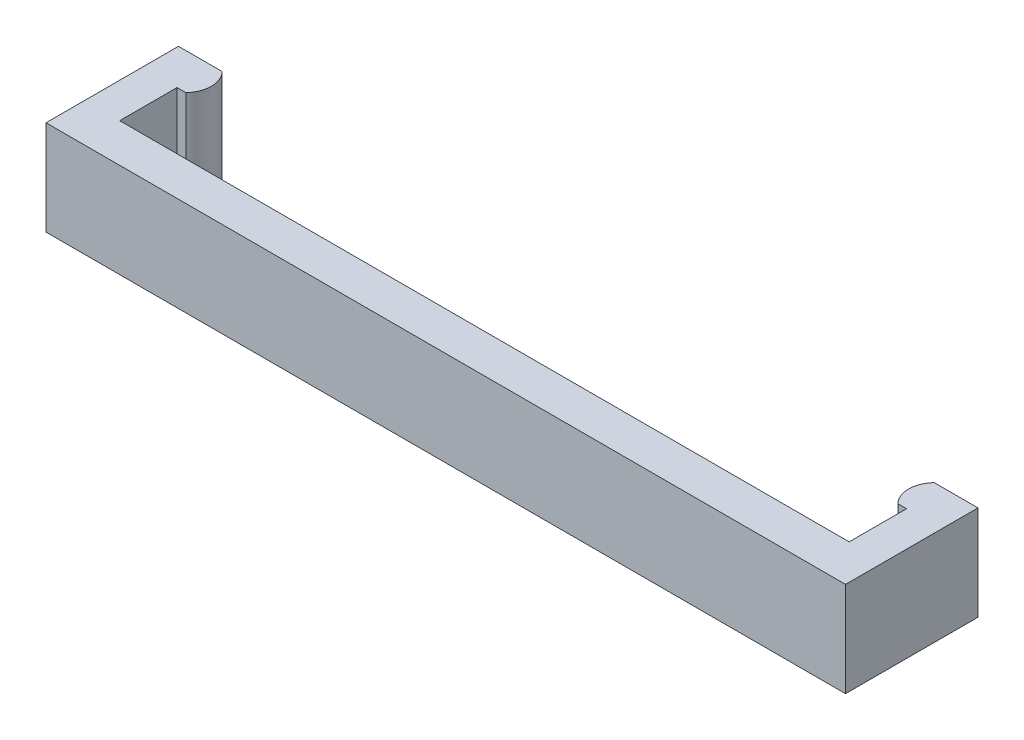
SolidWorks part; units mm, degrees
ref_plane "Front Plane" through (0, 0, 0) normal (0, 0, 1) x (1, 0, 0)
ref_plane "Top Plane" through (0, 0, 0) normal (0, 1, 0) x (1, 0, 0)
ref_plane "Right Plane" through (0, 0, 0) normal (1, 0, 0) x (0, 0, -1)
sketch "Sketch1" plane through (0, 0, 0) normal (0, -1, 0) x (1, 0, 0)
  line L0 (38.86, 36.51) -> (-11.94, 36.51) construction
  line L1 (38.86, 31.43) -> (38.86, 36.51) construction
  line L2 (37.86, 35.51) -> (37.86, 32.43) construction
  line L3 (-10.94, 35.51) -> (37.86, 35.51) construction
  line L4 (38.86, 36.51) -> (-11.94, 36.51)
  line L5 (38.86, 31.43) -> (38.86, 36.51)
  line L6 (37.86, 35.51) -> (37.86, 32.43)
  line L7 (-10.94, 35.51) -> (37.86, 35.51)
sketch "Sketch2" plane through (0, 0, 0) normal (0, -1, 0) x (1, 0, 0)
  line L0 (13.46, 38.51) -> (13.46, 36.51) construction
  line L1 (-13.94, 29.43) -> (40.86, 29.43)
  line L2 (-13.94, 29.43) -> (-13.94, 38.51)
  line L3 (-13.94, 38.51) -> (40.86, 38.51)
  line L4 (40.86, 29.43) -> (40.86, 38.51)
  line L5 (38.86, 36.51) -> (-11.94, 36.51) construction
  line L6 (40.86, 33.97) -> (38.86, 33.97) construction
  line L7 (38.86, 31.43) -> (38.86, 36.51) construction
  dimension "D1" = 2
  dimension "D2" = 2
extrude "Boss-Extrude1" add sketch "Sketch2" along normal up to surface (6.49 mm away)
sketch "Sketch3" plane through (0, 0, 0) normal (0, 1, 0) x (1, 0, 0)
  line L0 (-13.94, -29.43) -> (40.86, -29.43) construction
  line L1 (-11.54, -29.43) -> (38.46, -29.43)
  line L2 (-11.54, -29.43) -> (-11.54, -35.86)
  line L3 (-11.54, -35.86) -> (38.46, -35.86)
  line L4 (38.46, -29.43) -> (38.46, -35.86)
  line L5 (13.46, -36.51) -> (13.46, -35.86) construction
  line L6 (38.86, -36.51) -> (-11.94, -36.51) construction
  line L7 (38.86, -33.97) -> (38.46, -33.97) construction
  line L8 (38.86, -31.43) -> (38.86, -36.51) construction
  line L9 (37.86, -35.51) -> (37.86, -32.43) construction
  line L10 (-10.94, -35.51) -> (37.86, -35.51) construction
  dimension "D1" = 0.6
  dimension "D2" = 0.35
extrude "Cut-Extrude1" cut sketch "Sketch3" against normal through all
sketch "Sketch4" plane through (0, 0, 0) normal (0, 1, 0) x (1, 0, 0)
  line L0 (38.46, -29.43) -> (37.86, -29.43)
  line L1 (37.86, -31.93) -> (38.46, -31.93)
  line L2 (38.46, -35.86) -> (38.46, -29.43) construction
  line L3 (38.46, -31.93) -> (38.46, -29.43)
  line L4 (13.46, -38.51) -> (13.46, -27.5844) construction
  line L5 (40.86, -38.51) -> (-13.94, -38.51) construction
  line L6 (-10.94, -31.93) -> (-11.54, -31.93)
  line L7 (-11.54, -29.43) -> (-10.94, -29.43)
  line L8 (-11.54, -31.93) -> (-11.54, -29.43)
  line L9 (37.86, -35.51) -> (37.86, -32.43) construction
  arc A0 (37.86, -29.43) -> (37.86, -31.93) centre (39.1725, -30.68) ccw
  arc A1 (-10.94, -29.43) -> (-10.94, -31.93) centre (-12.2525, -30.68) cw
  point P17 (37.36, -30.68)
  point P18 (36.8116, -30.68)
  point P22 (0, 0)
  point P23 (37.7236, -29.43)
  dimension "D1" = 0.5
  dimension "D2" = 0.5
extrude "Boss-Extrude2" add sketch "Sketch4" against normal through all
